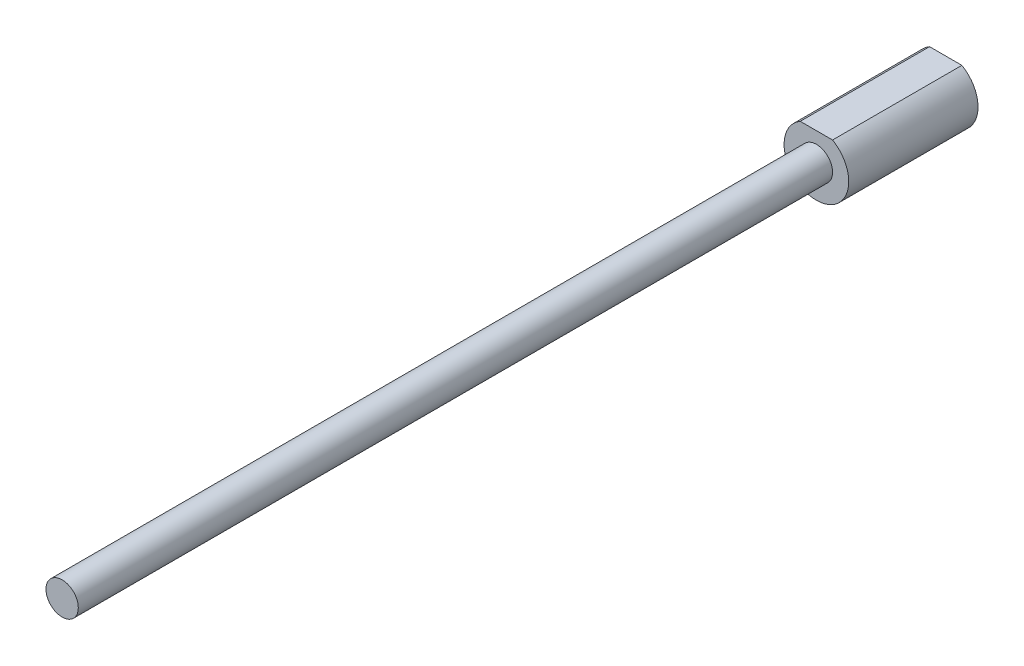
SolidWorks part; units mm, degrees
ref_plane "Спереди" through (0, 0, 0) normal (0, 0, 1) x (1, 0, 0)
ref_plane "Сверху" through (0, 0, 0) normal (0, 1, 0) x (1, 0, 0)
ref_plane "Справа" through (0, 0, 0) normal (1, 0, 0) x (0, 0, -1)
sketch "Эскиз2" plane through (0, 0, -28.1) normal (0, 0, -1) x (-1, 0, 0)
  line L0 (-0.75, 1.299) -> (0.75, 1.299)
  arc A0 (-0.75, 1.299) -> (0.75, 1.299) centre (0, 0) ccw
  dimension "D1" = 3
  dimension "D2" = 1.5
extrude "Бобышка-Вытянуть1" add sketch "Эскиз2" along normal blind 4 and the other way blind 2
sketch "Эскиз3" plane through (0, 0, -26.1) normal (0, 0, 1) x (1, 0, 0)
  circle A0 centre (0, 0) radius 0.75
  dimension "D1" = 1.5
extrude "Бобышка-Вытянуть2" add sketch "Эскиз3" along normal blind 35
